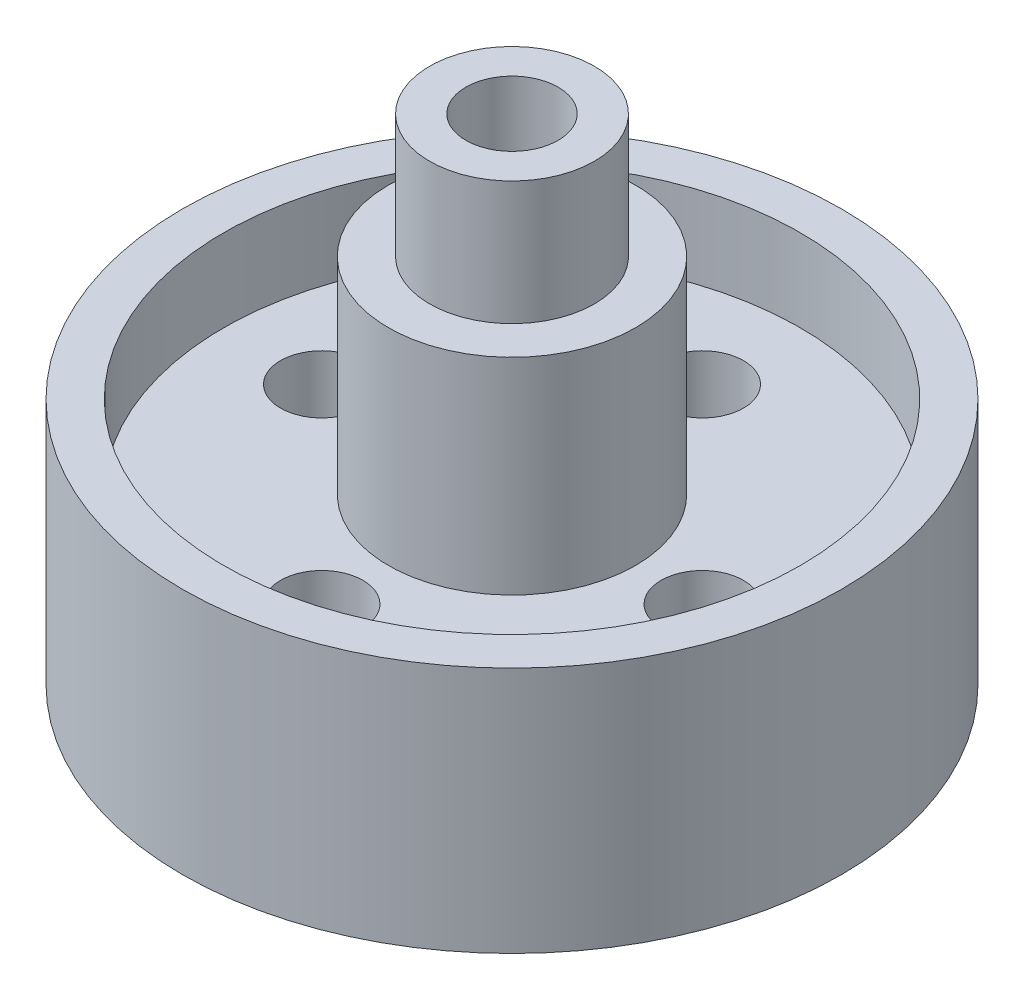
SolidWorks part; units mm, degrees
ref_plane "Front Plane" through (0, 0, 0) normal (0, 0, 1) x (1, 0, 0)
ref_plane "Top Plane" through (0, 0, 0) normal (0, 1, 0) x (1, 0, 0)
ref_plane "Right Plane" through (0, 0, 0) normal (1, 0, 0) x (0, 0, -1)
sketch "Sketch1" plane through (0, 0, 0) normal (0, 0, 1) x (1, 0, 0)
  line L0 (0, 0) -> (2000, 0)
  line L1 (2000, 0) -> (2000, 1500)
  line L2 (2000, 1500) -> (1750, 1500)
  line L4 (750, 2250) -> (500, 2250)
  line L5 (500, 2250) -> (500, 3000)
  line L6 (500, 3000) -> (0, 3000)
  line L7 (0, 3000) -> (0, 0)
  line L8 (1750, 1500) -> (1750, 1000)
  line L9 (1750, 1000) -> (750, 1000)
  line L11 (750, 2250) -> (750, 1000)
  line L12 (0, 0) -> (0, 4643.4748) construction
  dimension "D1" = 1500
  dimension "D2" = 2000
  dimension "D3" = 750
  dimension "D4" = 500
  dimension "D5" = 750
  dimension "D6" = 250
  dimension "D7" = 1250
  dimension "D8" = 1000
revolve "Revolve1" add sketch "Sketch1" angle 360 about L12
sketch "Sketch2" plane through (0, 3000, 0) normal (0, 1, 0) x (1, 0, 0)
  circle A0 centre (0, 0) radius 280
  dimension "D1" = 560
extrude "Cut-Extrude1" cut sketch "Sketch2" against normal through all
sketch "Sketch3" plane through (0, 1000, 0) normal (0, 1, 0) x (1, 0, 0)
  circle A0 centre (0, 0) radius 1155 construction
  circle A1 centre (1155, 0) radius 250
  dimension "D1" = 2310
  dimension "D2" = 500
extrude "Cut-Extrude2" cut sketch "Sketch3" against normal through all
pattern_circular "CirPattern1" count 4 over 360 about axis through (0, 0, 0) along (0, 1, 0) of "Cut-Extrude2"
